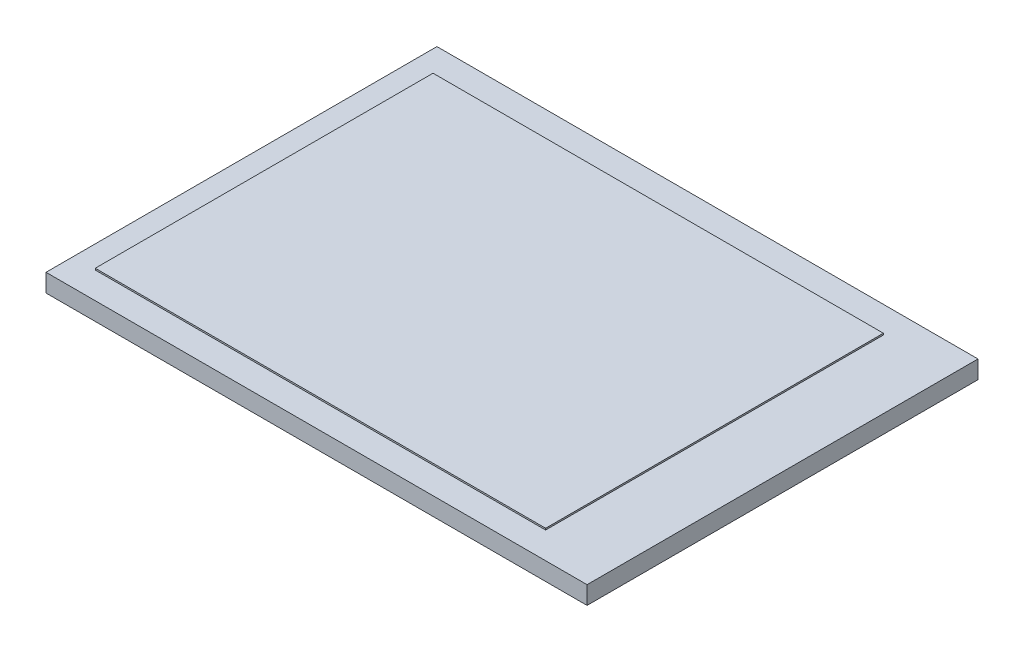
SolidWorks part; units mm, degrees
ref_plane "前视基准面" through (0, 0, 0) normal (0, 0, 1) x (1, 0, 0)
ref_plane "上视基准面" through (0, 0, 0) normal (0, 1, 0) x (1, 0, 0)
ref_plane "右视基准面" through (0, 0, 0) normal (1, 0, 0) x (0, 0, -1)
other "Configuration Table"
sketch "草图1" plane through (0, 0, 0) normal (0, 1, 0) x (1, 0, 0)
  line L1 (-34.6, -25) -> (34.6, -25)
  line L2 (-34.6, -25) -> (-34.6, 25)
  line L3 (-34.6, 25) -> (34.6, 25)
  line L4 (34.6, -25) -> (34.6, 25)
  line L5 (-34.6, -25) -> (34.6, 25) construction
  line L6 (-34.6, 25) -> (34.6, -25) construction
  point P0 (0, 0)
  dimension "D1" = 50
  dimension "D2" = 69.2
extrude "凸台-拉伸1" add sketch "草图1" along normal blind 2.3
sketch "草图2" plane through (0, 2.3, 0) normal (0, 1, 0) x (1, 0, 0)
  line L0 (-34.6, 0) -> (34.6, 0) construction
  line L1 (-34.6, 25) -> (-34.6, -25) construction
  line L2 (34.6, -25) -> (34.6, 25) construction
  line L3 (34.6, 0) -> (0, 25) construction
  line L4 (34.6, 25) -> (-34.6, 25) construction
  line L5 (0, 25) -> (0, -25) construction
  line L6 (-34.6, -25) -> (34.6, -25) construction
  line L8 (25.9, -21.6) -> (-31.7, -21.6)
  line L9 (25.9, -21.6) -> (25.9, 21.6)
  line L10 (25.9, 21.6) -> (-31.7, 21.6)
  line L11 (-31.7, -21.6) -> (-31.7, 21.6)
  line L12 (25.9, -21.6) -> (-31.7, 21.6) construction
  line L13 (25.9, 21.6) -> (-31.7, -21.6) construction
  point P12 (-2.9, 0)
  point P17 (0, 0)
  dimension "D1" = 57.6
  dimension "D2" = 43.2
  dimension "D3" = 2.9
extrude "凸台-拉伸2" add sketch "草图2" along normal blind 0.2
